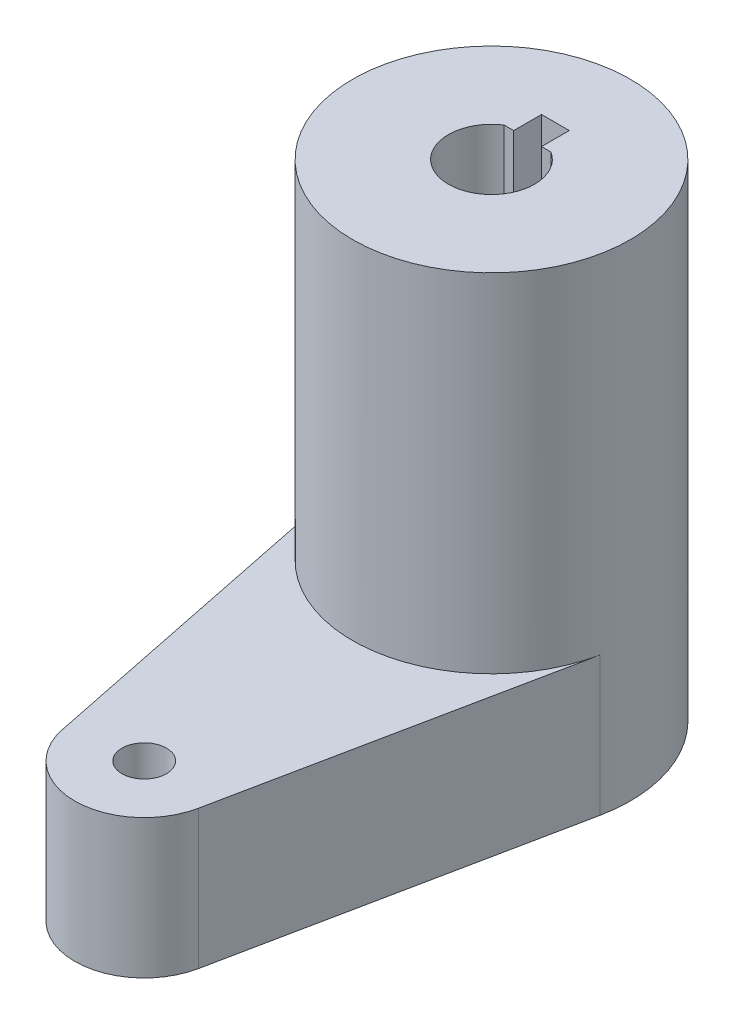
SolidWorks part; units mm, degrees
ref_plane "正面" through (0, 0, 0) normal (0, 0, 1) x (1, 0, 0)
ref_plane "平面" through (0, 0, 0) normal (0, 1, 0) x (1, 0, 0)
ref_plane "右側面" through (0, 0, 0) normal (1, 0, 0) x (0, 0, -1)
sketch "ｽｹｯﾁ1" plane through (0, 0, 0) normal (0, 1, 0) x (1, 0, 0)
  line L0 (-9.798, -2) -> (-4.899, -26)
  line L1 (4.899, -26) -> (9.798, -2)
  arc A0 (9.798, -2) -> (-9.798, -2) centre (0, 0) ccw
  arc A1 (-4.899, -26) -> (4.899, -26) centre (0, -25) ccw
  circle A2 centre (0, -25) radius 1.6
  dimension "D1" = 20
  dimension "D2" = 10
  dimension "D4" = 3.2
  dimension "D3" = 25
extrude "ﾎﾞｽ - 押し出し1" add sketch "ｽｹｯﾁ1" along normal blind 10
sketch "ｽｹｯﾁ3" plane through (0, 10, 0) normal (0, 1, 0) x (1, 0, 0)
  circle A0 centre (0, 0) radius 10
extrude "ﾎﾞｽ - 押し出し2" add sketch "ｽｹｯﾁ3" along normal blind 25
sketch "ｽｹｯﾁ2" plane through (0, 10, 0) normal (0, 1, 0) x (1, 0, 0)
  line L0 (-1.6882, 2.6) -> (-1, 2.6)
  line L7 (1, 2.6) -> (1.6882, 2.6)
  line L9 (-1, 2.6) -> (-1, 4.6)
  line L10 (-1, 4.6) -> (1, 4.6)
  line L11 (1, 2.6) -> (1, 4.6)
  line L12 (-1, 2.6) -> (1, 4.6) construction
  line L13 (-1, 4.6) -> (1, 2.6) construction
  arc A0 (-1.6882, 2.6) -> (1.6882, 2.6) centre (0, 0) ccw
  point P7 (0, 3.6)
  point P8 (0, 4.6)
  dimension "D1" = 2.6
  dimension "D2" = 6.2
  dimension "D3" = 2
  dimension "D4" = 2
extrude "ｶｯﾄ - 押し出し1" cut sketch "ｽｹｯﾁ2" against normal through all both and the other way through all
sketch "ｽｹｯﾁ4" plane through (0, 0, 0) normal (0, -1, 0) x (-1, 0, 0)
  line L0 (-4.2262, 9.0631) -> (0, 0)
  line L1 (0, 0) -> (4.2262, 9.0631)
  arc A1 (-4.2262, 9.0631) -> (4.2262, 9.0631) centre (0, 0) cw
  arc A2 (9.798, -2) -> (-9.798, -2) centre (0, 0) ccw construction
  point P8 (0, 10)
  dimension "D1" = 50
extrude "ｶｯﾄ - 押し出し2" cut sketch "ｽｹｯﾁ4" against normal offset from surface (25 mm away) 10 up to face at (0, 35, -2.3167)
